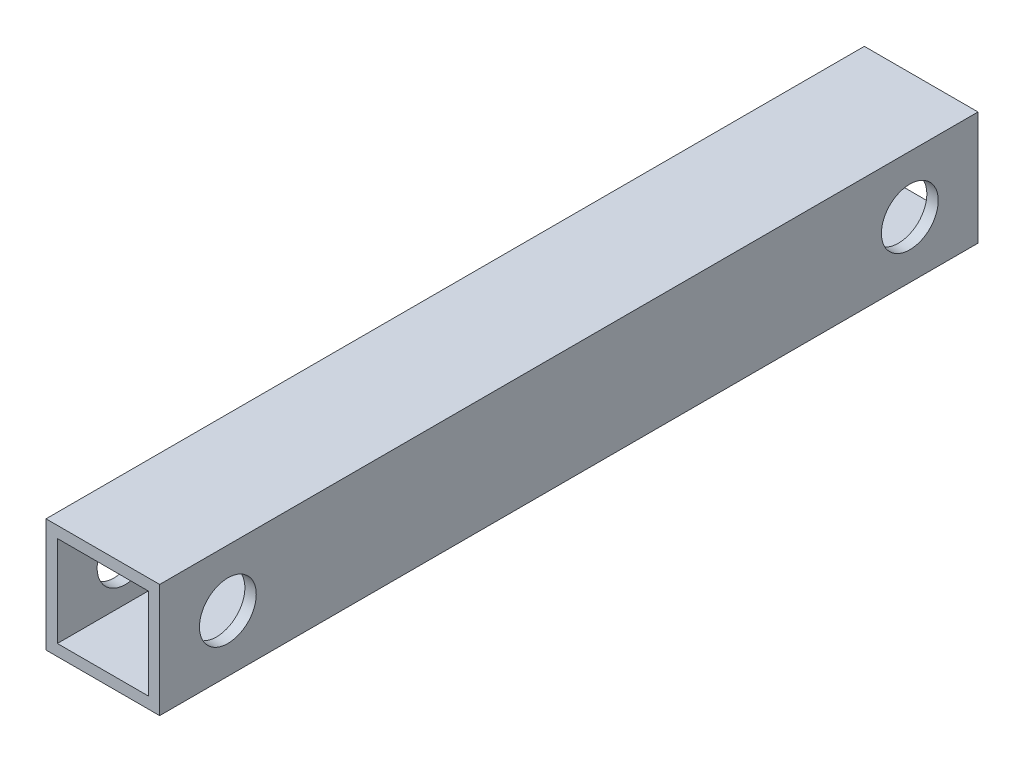
SolidWorks part; units mm, degrees
ref_plane "Front Plane" through (0, 0, 0) normal (0, 0, 1) x (1, 0, 0)
ref_plane "Top Plane" through (0, 0, 0) normal (0, 1, 0) x (1, 0, 0)
ref_plane "Right Plane" through (0, 0, 0) normal (1, 0, 0) x (0, 0, -1)
sketch "Sketch1" plane through (0, 0, 0) normal (0, 0, 1) x (1, 0, 0)
  line L1 (-25, -25) -> (25, -25)
  line L2 (-25, -25) -> (-25, 25)
  line L3 (-25, 25) -> (25, 25)
  line L4 (25, -25) -> (25, 25)
  line L5 (-25, -25) -> (25, 25) construction
  line L6 (-25, 25) -> (25, -25) construction
  line L7 (-20, -20) -> (20, -20)
  line L8 (-20, -20) -> (-20, 20)
  line L9 (-20, 20) -> (20, 20)
  line L10 (20, -20) -> (20, 20)
  line L11 (-20, -20) -> (20, 20) construction
  line L12 (-20, 20) -> (20, -20) construction
  point P0 (0, 0)
  point P6 (0, 0)
  dimension "D1" = 50
  dimension "0" = 50
  dimension "D2" = 40
  dimension "D3" = 40
extrude "Boss-Extrude1" add sketch "Sketch1" along normal blind 360
sketch "Sketch2" plane through (25, 0, 0) normal (1, 0, 0) x (0, 0, -1)
  line L0 (0, 0) -> (-360, 0) construction
  line L1 (-360, -25) -> (-360, 25) construction
  line L2 (0, -25) -> (0, 25) construction
  circle A0 centre (-330, 0) radius 12.5
  circle A1 centre (-30, 0) radius 12.5
  dimension "D3" = 25
  dimension "D4" = 25
  dimension "D1" = 30
  dimension "D2" = 30
extrude "Cut-Extrude1" cut sketch "Sketch2" against normal blind 300
